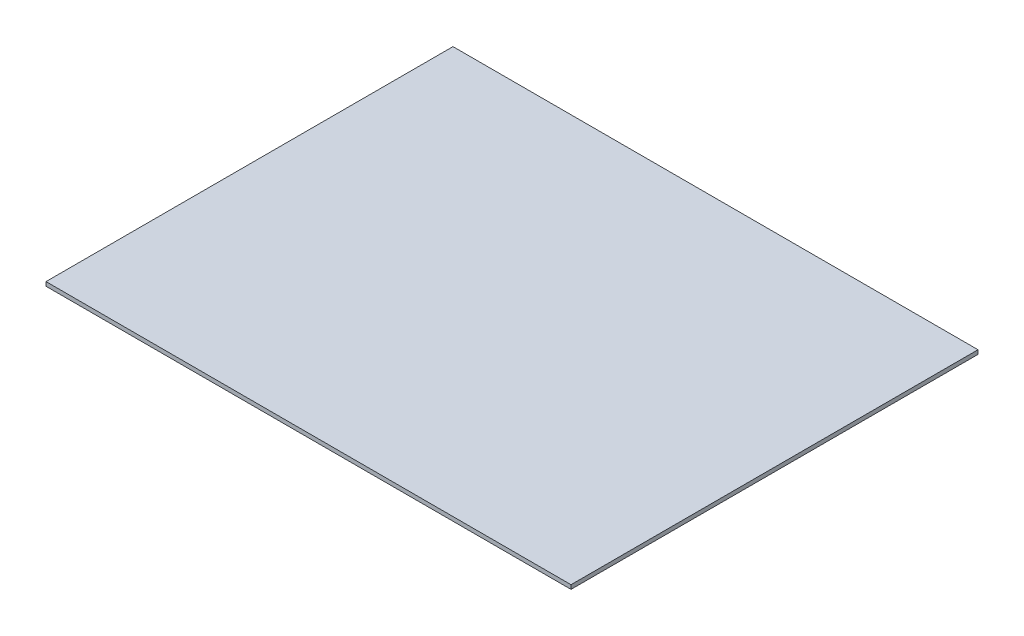
SolidWorks part; units mm, degrees
ref_plane "Front" through (0, 0, 0) normal (0, 0, 1) x (1, 0, 0)
ref_plane "Top" through (0, 0, 0) normal (0, 1, 0) x (1, 0, 0)
ref_plane "Right" through (0, 0, 0) normal (1, 0, 0) x (0, 0, -1)
sketch "Sketch1" plane through (0, 0, 0) normal (0, 0, 1) x (1, 0, 0)
  line L1 (-322.5, -60) -> (322.5, -60)
  line L2 (-322.5, -60) -> (-322.5, -55)
  line L3 (-322.5, -55) -> (322.5, -55)
  line L4 (322.5, -60) -> (322.5, -55)
extrude "Base-Extrude" add sketch "Sketch1" along normal up to surface (500 mm away)
